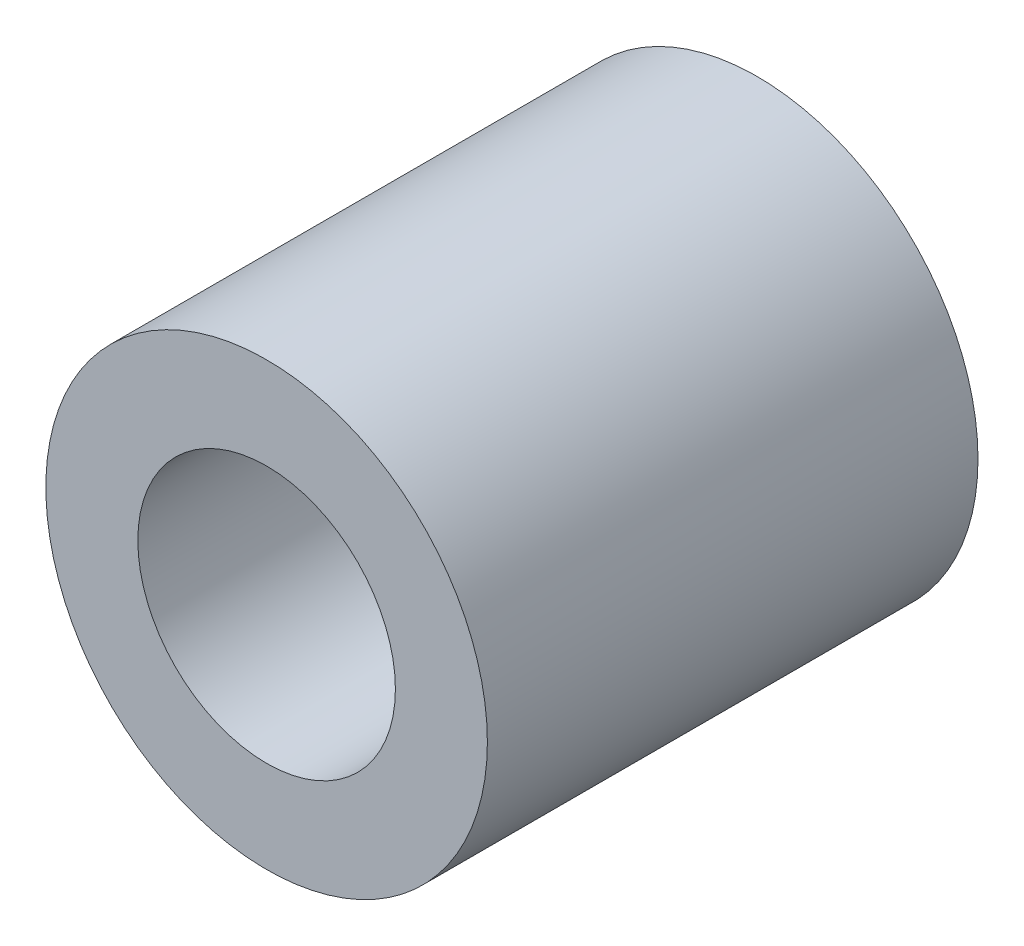
SolidWorks part; units mm, degrees
ref_plane "前视基准面" through (0, 0, 0) normal (0, 0, 1) x (1, 0, 0)
ref_plane "上视基准面" through (0, 0, 0) normal (0, 1, 0) x (1, 0, 0)
ref_plane "右视基准面" through (0, 0, 0) normal (1, 0, 0) x (0, 0, -1)
sketch "草图1" plane through (0, 0, 0) normal (0, 0, 1) x (1, 0, 0)
  circle A0 centre (0, 0) radius 9
  circle A1 centre (0, 0) radius 5.25
  dimension "D1" = 18
  dimension "D2" = 10.5
extrude "拉伸1" add sketch "草图1" along normal blind 20
